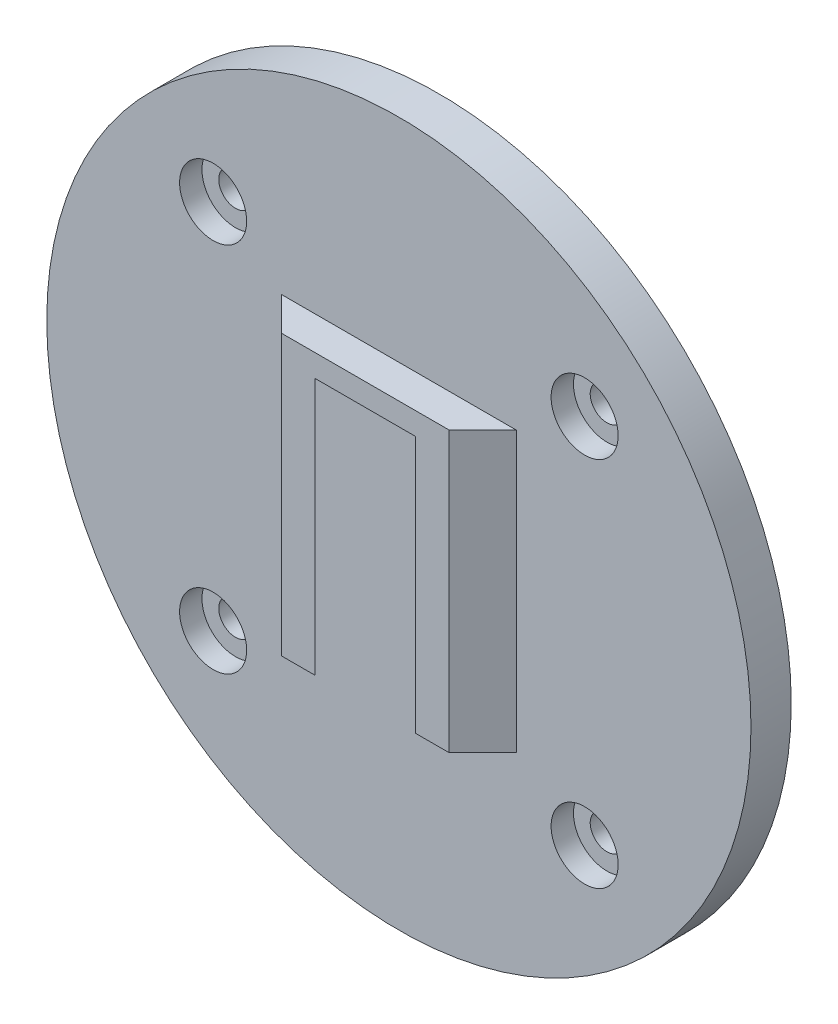
SolidWorks part; units mm, degrees
ref_plane "Alzado" through (0, 0, 0) normal (0, 0, 1) x (1, 0, 0)
ref_plane "Planta" through (0, 0, 0) normal (0, 1, 0) x (1, 0, 0)
ref_plane "Vista lateral" through (0, 0, 0) normal (1, 0, 0) x (0, 0, -1)
sketch "Croquis1" plane through (0, 0, 0) normal (0, 0, 1) x (1, 0, 0)
  circle A0 centre (-75.6653, 11.3234) radius 31.5
extrude "Saliente-Extruir1" add sketch "Croquis1" along normal blind 3.6
sketch "Croquis2" plane through (0, 0, 3.6) normal (0, 0, 1) x (1, 0, 0)
  line L0 (-75.6653, 11.3234) -> (-53.3914, 33.5973) construction
  line L1 (-53.3914, 33.5973) -> (-97.9391, 33.5973) construction
  line L2 (-97.9391, 33.5973) -> (-53.3914, -10.9504) construction
  line L3 (-53.3914, -10.9504) -> (-97.9391, -10.9504) construction
  line L4 (-97.9391, -10.9504) -> (-75.6653, 11.3234) construction
  circle A0 centre (-75.6653, 11.3234) radius 31.5 construction
  circle A1 centre (-92.2823, 27.9404) radius 1.5
  circle A3 centre (-59.0483, 27.9404) radius 1.5
  circle A4 centre (-59.0483, -5.2936) radius 1.5
  circle A5 centre (-92.2823, -5.2936) radius 1.5
  dimension "D1" = 8
extrude "Cortar-Extruir1" cut sketch "Croquis2" against normal blind 3.6
sketch "Croquis3" plane through (0, 0, 3.6) normal (0, 0, 1) x (1, 0, 0)
  circle A0 centre (-92.2823, 27.9404) radius 3
  circle A1 centre (-59.0483, 27.9404) radius 3
  circle A2 centre (-59.0483, -5.2936) radius 3
  circle A3 centre (-92.2823, -5.2936) radius 3
extrude "Cortar-Extruir2" cut sketch "Croquis3" against normal blind 2
sketch "Croquis4" plane through (0, 0, 3.6) normal (0, 0, 1) x (1, 0, 0)
  line L1 (-83.1653, -1.1766) -> (-68.1653, -1.1766)
  line L2 (-83.1653, -1.1766) -> (-83.1653, 23.8234)
  line L3 (-83.1653, 23.8234) -> (-68.1653, 23.8234)
  line L4 (-68.1653, -1.1766) -> (-68.1653, 23.8234)
  line L5 (-83.1653, -1.1766) -> (-68.1653, 23.8234) construction
  line L6 (-83.1653, 23.8234) -> (-68.1653, -1.1766) construction
  point P0 (-75.6653, 11.3234)
  dimension "D1" = 15
  dimension "D2" = 25
extrude "Saliente-Extruir2" add sketch "Croquis4" along normal blind 3
sketch "Croquis7" plane through (0, -1.1766, 0) normal (0, -1, 0) x (1, 0, 0)
  line L0 (-83.1653, 6.6) -> (-86.1653, 3.6)
  line L1 (-86.1653, 3.6) -> (-83.1653, 3.6)
  line L2 (-83.1653, 3.6) -> (-83.1653, 6.6)
  line L3 (-68.1653, 6.6) -> (-65.1653, 3.6)
  line L4 (-65.1653, 3.6) -> (-68.1653, 3.6)
  line L5 (-68.1653, 3.6) -> (-68.1653, 6.6)
extrude "Saliente-Extruir4" add sketch "Croquis7" against normal up to vertex (25 mm away)
sketch "Croquis8" plane through (0, -1.1766, 0) normal (0, -1, 0) x (1, 0, 0)
  line L0 (-83.1653, 6.6) -> (-83.1653, 3.6) construction
  line L1 (-86.1653, 3.6) -> (-65.1653, 3.6) construction
  line L2 (-83.1653, 3.6) -> (-68.1653, 3.6) construction
  line L3 (-83.1653, 3.6) -> (-80.1653, 6.6)
  line L4 (-83.1653, 6.6) -> (-68.1653, 6.6) construction
  line L5 (-68.1653, 3.6) -> (-71.1653, 6.6)
  line L6 (-71.1653, 6.6) -> (-80.1653, 6.6)
  line L7 (-83.1653, 3.6) -> (-68.1653, 3.6)
extrude "Cortar-Extruir6" cut sketch "Croquis8" against normal blind 23
